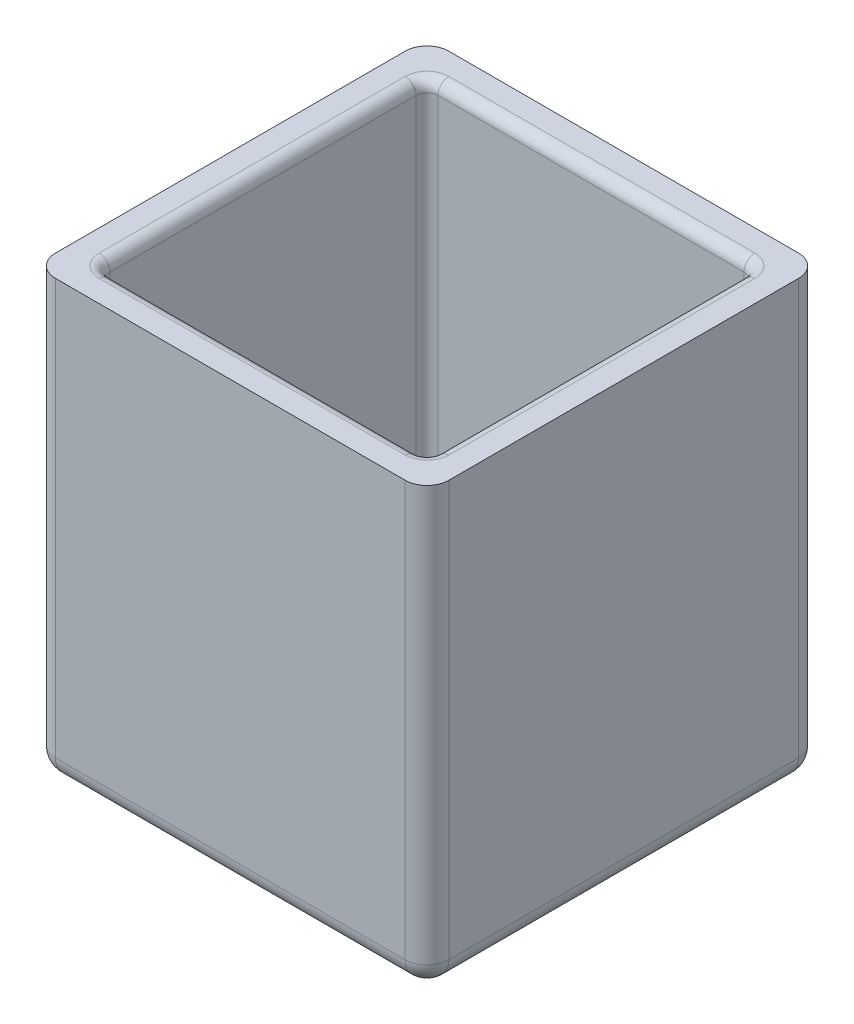
SolidWorks part; units mm, degrees
material "PBT General Purpose"
ref_plane "Front Plane" through (0, 0, 0) normal (0, 0, 1) x (1, 0, 0)
ref_plane "Top Plane" through (0, 0, 0) normal (0, 1, 0) x (1, 0, 0)
ref_plane "Right Plane" through (0, 0, 0) normal (1, 0, 0) x (0, 0, -1)
sketch "Sketch1" plane through (0, 0, 0) normal (0, 1, 0) x (1, 0, 0)
  line L0 (0, 0) -> (36, 0)
  line L1 (0, 0) -> (0, 36)
  line L2 (36, 0) -> (36, 36)
  line L3 (0, 36) -> (36, 36)
  line L4 (3, 33) -> (33, 33)
  line L5 (3, 33) -> (3, 3)
  line L6 (33, 33) -> (33, 3)
  line L7 (3, 3) -> (33, 3)
  dimension "D1" = 3
  dimension "D2" = 3
  dimension "D3" = 3
  dimension "D4" = 3
  dimension "D5" = 30
  dimension "D6" = 30
extrude "Boss-Extrude1" add sketch "Sketch1" along normal blind 40
sketch "Sketch2" plane through (0, 0, 0) normal (0, -1, 0) x (1, 0, 0)
  line L0 (33, -33) -> (33, -3) construction
  line L1 (3, -3) -> (33, -3) construction
  line L2 (3, -33) -> (3, -3) construction
  line L3 (3, -33) -> (33, -33) construction
  line L4 (33, -33) -> (33, -3)
  line L5 (3, -3) -> (33, -3)
  line L6 (3, -33) -> (3, -3)
  line L7 (3, -33) -> (33, -33)
extrude "Boss-Extrude2" add sketch "Sketch2" against normal blind 3
fillet "Скругление1" radius 2 4 edges at (0, 20, -36) (0, 20, 0) (36, 20, -36) (36, 20, 0)
fillet "Скругление2" radius 2 8 edges at (35.4142, 0, -0.5858) (18, 0, 0) (0.5858, 0, -0.5858) (0, 0, -18) (0.5858, 0, -35.4142) (18, 0, -36) (35.4142, 0, -35.4142) (36, 0, -18)
sketch "Эскиз1" plane through (0, 0, 0) normal (0, -1, 0) x (1, 0, 0)
  line L0 (2, -18) -> (34, -18) construction
  line L1 (2, -2) -> (2, -34) construction
  line L2 (34, -34) -> (34, -2) construction
  line L3 (18, -2) -> (18, -34) construction
  line L4 (34, -2) -> (2, -2) construction
  line L5 (2, -34) -> (34, -34) construction
fillet "Скругление3" radius 1 12 edges at (18, 40, -3) (33, 40, -18) (3, 40, -18) (33, 3, -18) (18, 3, -3) (3, 3, -18) (18, 40, -33) (33, 21.5, -33) (18, 3, -33) (3, 21.5, -33) (33, 21.5, -3) (3, 21.5, -3)
